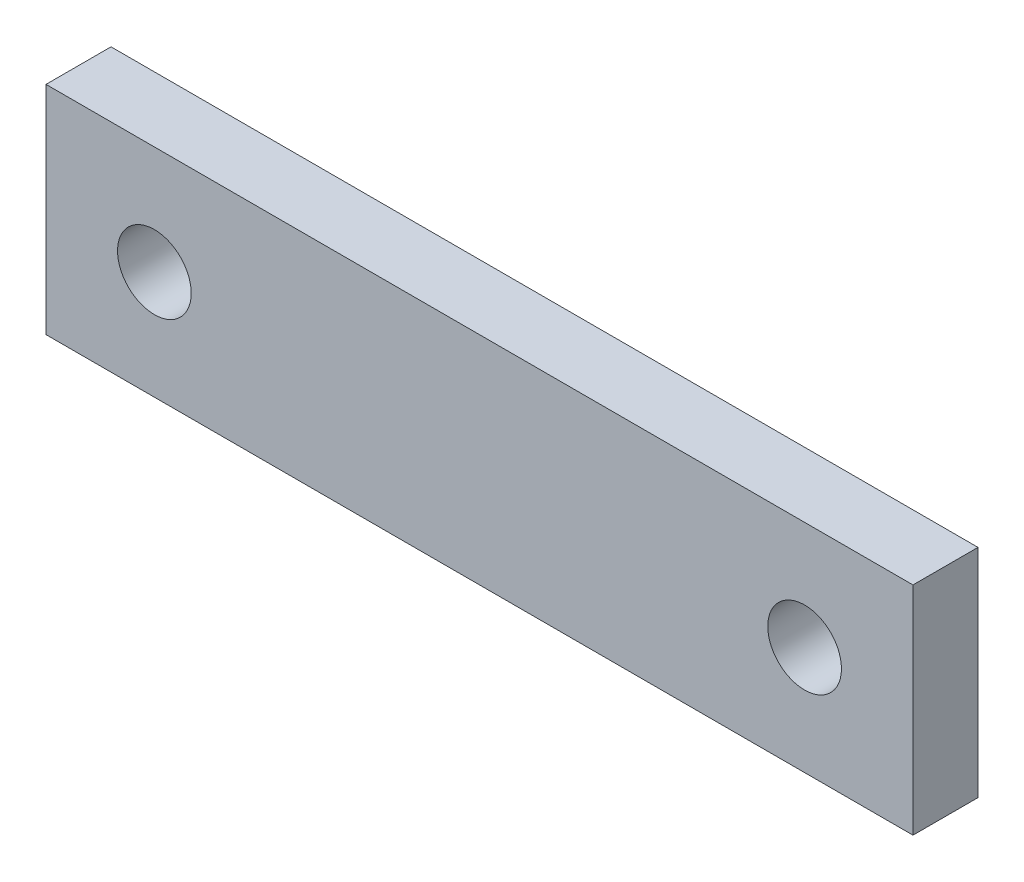
SolidWorks part; units mm, degrees
other "Platform Joint Strap 1 Right"
ref_plane "Front Plane" through (0, 0, 0) normal (0, 0, 1) x (1, 0, 0)
ref_plane "Top Plane" through (0, 0, 0) normal (0, 1, 0) x (1, 0, 0)
ref_plane "Right Plane" through (0, 0, 0) normal (1, 0, 0) x (0, 0, -1)
sketch3d "Main Profile Sketch datum points"
  point P0 (0, 0, 44.5)
  point P1 (10, 0, 44.5)
  point P2 (0, 10, 44.5)
ref_plane "Main Profile Sketch plane" through (0, 0, 44.5) normal (0, 0, 1) x (1, 0, 0)
sketch "Main Profile Sketch" plane through (0, 0, 44.5) normal (0, 0, 1) x (1, 0, 0)
  line L0 (-130, -31.5) -> (-90, -31.5)
  line L1 (-90, -31.5) -> (-90, -41.5)
  line L2 (-130, -41.5) -> (-90, -41.5)
  line L3 (-130, -31.5) -> (-130, -41.5)
  circle A0 centre (-125, -36.5) radius 1.7
  circle A1 centre (-95, -36.5) radius 1.7
extrude "Main Extrusion" add sketch "Main Profile Sketch" against normal blind 3 separate body
